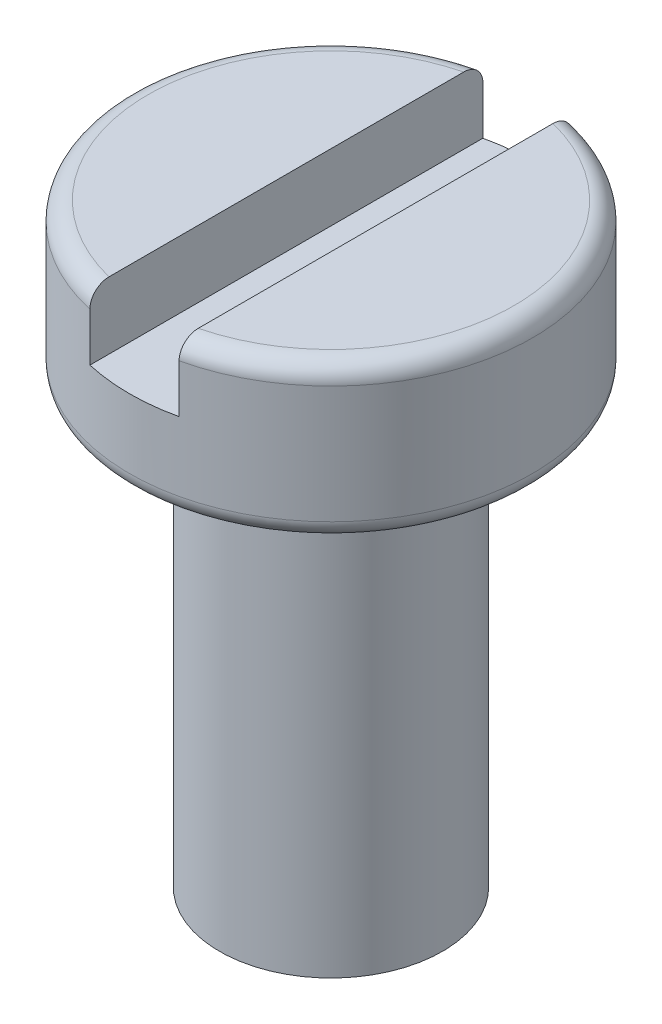
SolidWorks part; units mm, degrees
material "Plain Carbon Steel"
ref_plane "Front Plane" through (0, 0, 0) normal (0, 0, 1) x (1, 0, 0)
ref_plane "Top Plane" through (0, 0, 0) normal (0, 1, 0) x (1, 0, 0)
ref_plane "Right Plane" through (0, 0, 0) normal (1, 0, 0) x (0, 0, -1)
sketch "Sketch1" plane through (0, 0, 0) normal (0, 1, 0) x (1, 0, 0)
  circle A0 centre (0, 0) radius 2.71
  dimension "D1" = 5.42
extrude "Boss-Extrude1" add sketch "Sketch1" along normal blind 8
sketch "Sketch2" plane through (0, 8, 0) normal (0, 1, 0) x (1, 0, 0)
  circle A0 centre (0, 0) radius 1.5
  dimension "D1" = 3
extrude "Cut-Extrude1" cut sketch "Sketch2" against normal blind 5.92 flip side to cut
cosmetic thread "Cosmetic Thread1" parameters "D2"=2.439
fillet "Fillet1" radius 0.25 2 edges at (0, 0, 2.71) (0, 2.08, 2.71)
fillet "Fillet2" radius 0.15 1 edges at (0, 2.08, 1.5)
sketch "Sketch3" plane through (0, 0, 0) normal (0, -1, 0) x (1, 0, 0)
  line L0 (0, 2.71) -> (0, -2.71) construction
  line L1 (-0.6, -2.711) -> (-0.6, 2.711)
  line L2 (-0.6, -2.711) -> (0.6, -2.711)
  line L3 (-0.6, 2.711) -> (0.6, 2.711)
  line L4 (0.6, -2.711) -> (0.6, 2.711)
  line L5 (-0.6, -2.711) -> (0.6, 2.711) construction
  line L6 (-0.6, 2.711) -> (0.6, -2.711) construction
  circle A0 centre (0, 0) radius 2.71 construction
  point P6 (0, 0)
  dimension "D1" = 0.6
extrude "Cut-Extrude2" cut sketch "Sketch3" against normal blind 0.9
move or copy body "Body-Move/Copy1" bodies to move or copy 103 copy no rotation origin (0, 10, 0) rotation axis (1, 0, 0) rotation angle 180
